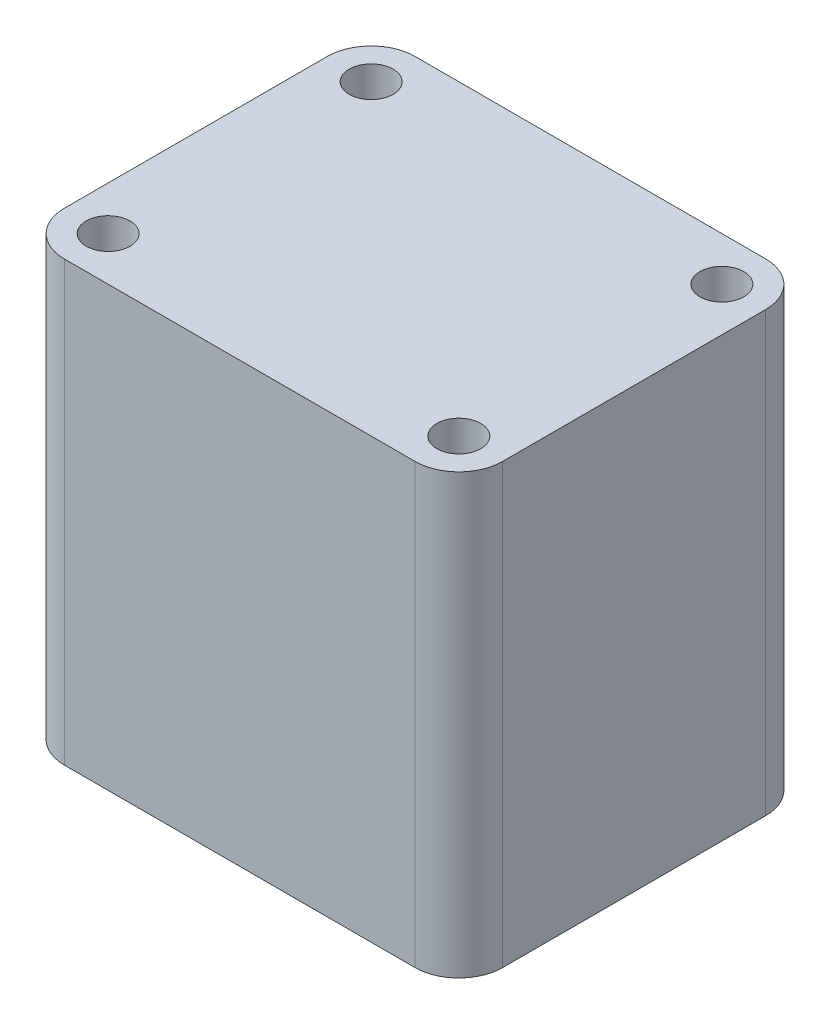
SolidWorks part; units mm, degrees
ref_plane "Alzado" through (0, 0, 0) normal (0, 0, 1) x (1, 0, 0)
ref_plane "Planta" through (0, 0, 0) normal (0, 1, 0) x (1, 0, 0)
ref_plane "Vista lateral" through (0, 0, 0) normal (1, 0, 0) x (0, 0, -1)
sketch "Croquis1" plane through (0, 0, 0) normal (0, 1, 0) x (1, 0, 0)
  line L0 (0, 40) -> (0, -40) construction
  line L1 (-50, 40) -> (50, 40)
  line L2 (-50, 40) -> (-50, -40)
  line L3 (-50, -40) -> (50, -40)
  line L4 (50, 40) -> (50, -40)
  dimension "D1" = 100
  dimension "D2" = 80
extrude "Saliente-Extruir1" add sketch "Croquis1" along normal blind 100
fillet "Redondeo1" radius 10 4 edges at (-50, 50, -40) (50, 50, -40) (50, 50, 40) (-50, 50, 40)
sketch "Croquis2" plane through (0, 100, 0) normal (0, 1, 0) x (1, 0, 0)
  circle A0 centre (-40, 30) radius 5
  dimension "D1" = 10
extrude "Cortar-Extruir1" cut sketch "Croquis2" against normal through all
mirror "Simetría1" about plane through (0, 0, 0) normal (0, 0, 1) of "Cortar-Extruir1" second plane through (0, 0, 0) second plane normal (1, 0, 0)
equation "\"Width\"= 100"
equation "\"Depth\"= 80"
equation "\"Height\"= 50"
equation "\"Height\"= 100"
equation "\"D1@Croquis1\"=\"Width\""
equation "\"D2@Croquis1\"=\"Depth\""
equation "\"D1@Saliente-Extruir1\"=\"Height\""
